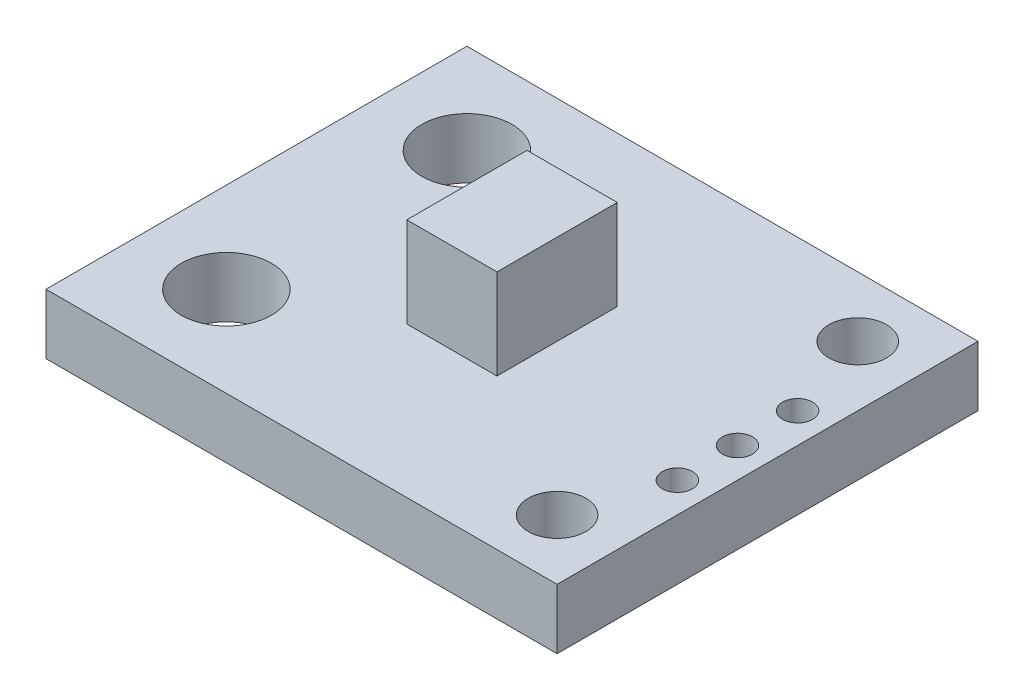
SolidWorks part; units mm, degrees
ref_plane "Front Plane" through (0, 0, 0) normal (0, 0, 1) x (1, 0, 0)
ref_plane "Top Plane" through (0, 0, 0) normal (0, 1, 0) x (1, 0, 0)
ref_plane "Right Plane" through (0, 0, 0) normal (1, 0, 0) x (0, 0, -1)
sketch "Sketch1" plane through (0, 0, 0) normal (0, 1, 0) x (1, 0, 0)
  line L1 (-10.795, 8.89) -> (10.795, 8.89)
  line L2 (-10.795, 8.89) -> (-10.795, -8.89)
  line L3 (-10.795, -8.89) -> (10.795, -8.89)
  line L4 (10.795, 8.89) -> (10.795, -8.89)
  line L5 (-10.795, 8.89) -> (10.795, -8.89) construction
  line L6 (-10.795, -8.89) -> (10.795, 8.89) construction
  point P0 (0, 0)
  dimension "D1" = 21.59
  dimension "D2" = 17.78
extrude "Boss-Extrude1" add sketch "Sketch1" along normal blind 2.54
sketch "Sketch2" plane through (0, 2.54, 0) normal (0, 1, 0) x (1, 0, 0)
  line L0 (-10.795, 8.89) -> (-10.795, -8.89) construction
  line L1 (-10.795, -8.89) -> (10.795, -8.89) construction
  line L2 (10.795, 8.89) -> (-10.795, 8.89) construction
  line L3 (9.525, 2.54) -> (9.525, -2.54) construction
  line L4 (0, 0) -> (9.525, 0) construction
  line L5 (10.795, -8.89) -> (10.795, 8.89) construction
  circle A0 centre (-6.985, 5.08) radius 1.905
  circle A1 centre (-6.985, -5.08) radius 1.905
  circle A2 centre (9.525, 2.54) radius 0.635
  circle A3 centre (9.525, 0) radius 0.635
  circle A5 centre (9.525, -2.54) radius 0.635
  dimension "D1" = 3.81
  dimension "D5" = 2.54
  dimension "D8" = 1.27
  dimension "D9" = 1.27
  dimension "D2" = 3.81
  dimension "D3" = 3.81
  dimension "D4" = 3.81
extrude "Cut-Extrude1" cut sketch "Sketch2" against normal through all
sketch "Sketch3" plane through (0, 2.54, 0) normal (0, 1, 0) x (1, 0, 0)
  line L1 (-1.905, 2.54) -> (1.905, 2.54)
  line L2 (-1.905, 2.54) -> (-1.905, -2.54)
  line L3 (-1.905, -2.54) -> (1.905, -2.54)
  line L4 (1.905, 2.54) -> (1.905, -2.54)
  line L5 (-1.905, 2.54) -> (1.905, -2.54) construction
  line L6 (-1.905, -2.54) -> (1.905, 2.54) construction
  point P0 (0, 0)
  dimension "D1" = 5.08
  dimension "D2" = 3.81
extrude "Boss-Extrude2" add sketch "Sketch3" along normal blind 3.81
hole_wizard "#2 Clearance Hole1" positions "Sketch5" profile "Sketch4" hole size "#2" standard "ANSI Inch"
sketch "Sketch5" plane through (0, 2.54, 0) normal (0, 1, 0) x (1, 0, 0)
  line L0 (8.255, 6.35) -> (8.255, -6.35) construction
  line L1 (0, 0) -> (8.255, 0) construction
  line L3 (10.795, -8.89) -> (10.795, 8.89) construction
  point P0 (8.255, 6.35)
  point P1 (8.255, -6.35)
  dimension "D1" = 12.7
  dimension "D2" = 2.54
sketch "Sketch4" plane through (8.255, 2.54, -6.35) normal (1, 0, 0) x (0, 0, 1)
  line L0 (0, 0) -> (0, 7.0826)
  line L1 (0, 7.0826) -> (1.2192, 6.35)
  line L2 (1.2192, 6.35) -> (1.2192, 0)
  line L5 (1.2192, 0) -> (0, 0)
  line L10 (0, 7.0826) -> (-1.2192, 6.35) construction
  line L11 (0, -6.35) -> (0, 107.95) construction
  dimension "Hole Dia." = 2.4384
  dimension "Hole Depth" = 6.35
  dimension "Drill Angle" = 118
